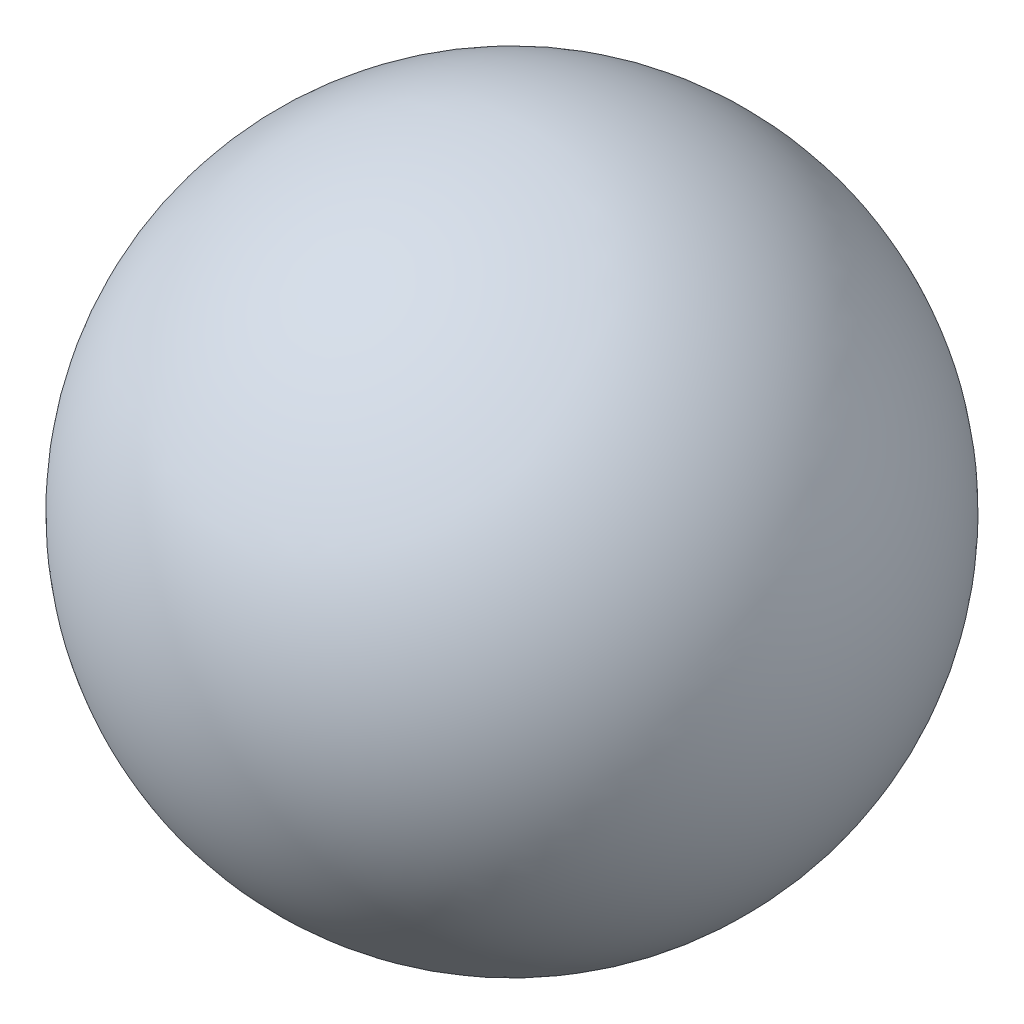
SolidWorks part; units mm, degrees
ref_plane "Front Plane" through (0, 0, 0) normal (0, 0, 1) x (1, 0, 0)
ref_plane "Top Plane" through (0, 0, 0) normal (0, 1, 0) x (1, 0, 0)
ref_plane "Right Plane" through (0, 0, 0) normal (1, 0, 0) x (0, 0, -1)
sketch "Sketch2" plane through (0, 0, 0) normal (0, 1, 0) x (1, 0, 0)
  line L0 (0, 43.481) -> (0, -44.0906)
  arc A0 (0, 25.4) -> (0, -25.4) centre (0, 0) ccw
revolve "Revolve-Thin4" add sketch "Sketch2" angle 360 about L0
